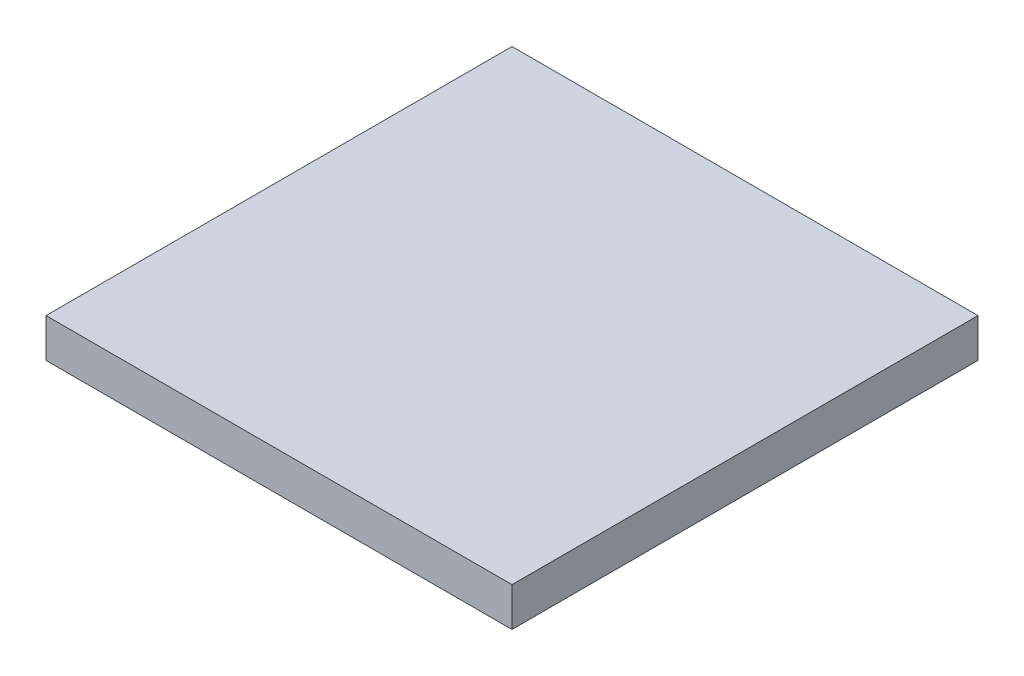
SolidWorks part; units mm, degrees
ref_plane "前视基准面" through (0, 0, 0) normal (0, 0, 1) x (1, 0, 0)
ref_plane "上视基准面" through (0, 0, 0) normal (0, 1, 0) x (1, 0, 0)
ref_plane "右视基准面" through (0, 0, 0) normal (1, 0, 0) x (0, 0, -1)
sketch "草图1" plane through (0, 0, 0) normal (0, 1, 0) x (1, 0, 0)
  line L0 (0, 0) -> (120, 0)
  line L1 (0, 0) -> (0, -120)
  line L2 (120, 0) -> (120, -120)
  line L3 (0, -120) -> (120, -120)
extrude "凸台-拉伸1" add sketch "草图1" along normal blind 10
